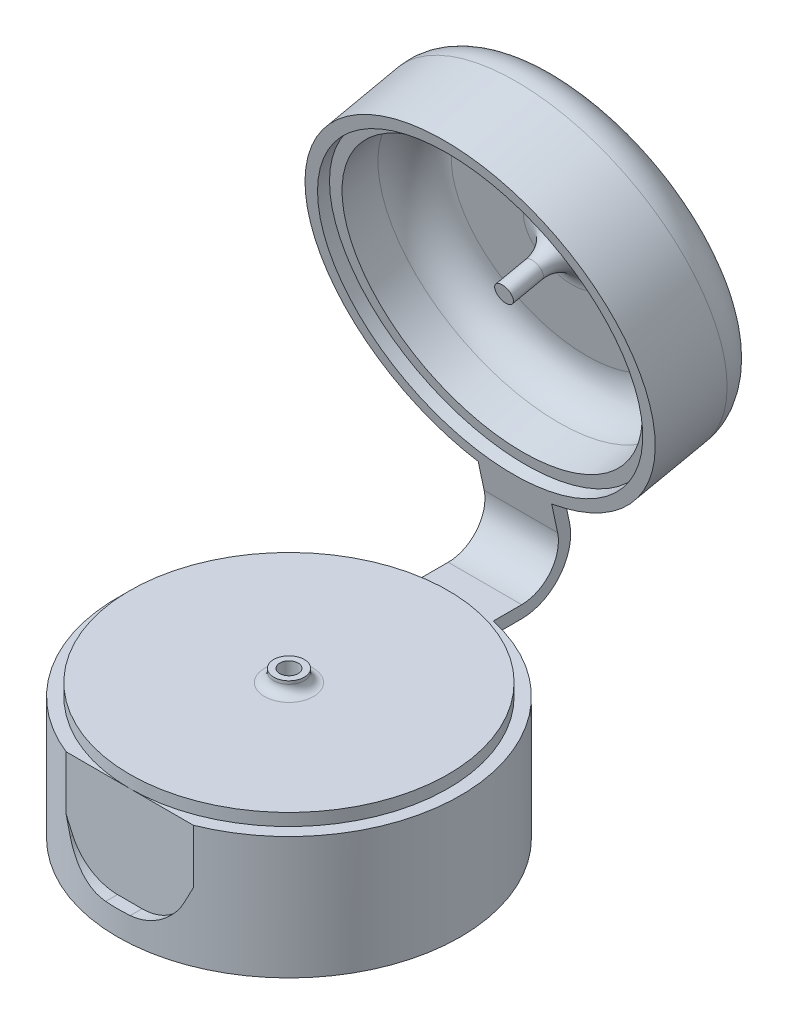
SolidWorks part; units mm, degrees
material "Polyethylene Cross-Linked"
ref_plane "Front Plane" through (0, 0, 0) normal (0, 0, 1) x (1, 0, 0)
ref_plane "Top Plane" through (0, 0, 0) normal (0, 1, 0) x (1, 0, 0)
ref_plane "Right Plane" through (0, 0, 0) normal (1, 0, 0) x (0, 0, -1)
sketch "Sketch1" plane through (0, 0, 0) normal (1, 0, 0) x (0, 0, -1)
  line L0 (0, 0) -> (0, -5.1961) construction
  line L1 (-2, 0) -> (-13, 0)
  line L2 (-13, 0) -> (-13, -1)
  line L3 (-13, -1) -> (-14, -1)
  line L4 (-14, -1) -> (-14, -11)
  line L7 (-14, -11) -> (-12, -11)
  line L8 (-12, -11) -> (-12, -2)
  line L9 (-12, -2) -> (-2, -2)
  line L13 (-2, 0) -> (-2, -2)
  dimension "D2" = 1
  dimension "D3" = 1
  dimension "D1" = 28
  dimension "D4" = 11
  dimension "D5" = 2
  dimension "D6" = 2
  dimension "D7" = 4
revolve "Revolve1" add sketch "Sketch1" angle 360 about L0
ref_plane "Plane1" through (0, 0, 13) normal (0, 0, 1) x (1, 0, 0)
sketch "Sketch3" plane through (0, 0, 13) normal (0, 0, 1) x (1, 0, 0)
  line L0 (0, -1) -> (0, -9) construction
  line L1 (14, -1) -> (-14, -1) construction
  line L2 (1, -9) -> (-1, -9)
  line L3 (-4.6542, -6.6269) -> (-7.1595, -1)
  line L4 (-7.1595, -1) -> (7.1595, -1)
  line L5 (-14, -11) -> (14, -11) construction
  line L6 (4.6542, -6.6269) -> (7.1595, -1)
  arc A0 (-1, -9) -> (-4.6542, -6.6269) centre (-1, -5) cw
  arc A1 (1, -9) -> (4.6542, -6.6269) centre (1, -5) ccw
  dimension "D1" = 4
  dimension "D2" = 2
  dimension "D3" = 48
  dimension "D4" = 2
extrude "Cut-Extrude1" cut sketch "Sketch3" along normal blind 8.5 from surface at 0 starting at plane "Plane1"
sketch "Sketch4" plane through (0, 0, 0) normal (1, 0, 0) x (0, 0, -1)
  line L0 (13, -1) -> (16, -1)
  line L1 (14, -1) -> (-13, -1) construction
  line L2 (18.9344, 2.6237) -> (18.3107, 5.5582)
  line L3 (18.3107, 5.5582) -> (19.2889, 5.7661)
  line L4 (19.2889, 5.7661) -> (19.9126, 2.8316)
  line L5 (16, -2) -> (13, -2)
  line L6 (13, -2) -> (13, -1)
  arc A0 (16, -1) -> (18.9344, 2.6237) centre (16, 2) ccw
  arc A1 (19.9126, 2.8316) -> (16, -2) centre (16, 2) cw
  dimension "D3" = 3
  dimension "D1" = 1
  dimension "D4" = 3
  dimension "D5" = 3
  dimension "D2" = 78
extrude "Boss-Extrude1" add sketch "Sketch4" along normal mid plane 6
sketch "Sketch5" plane through (0, 0, 0) normal (1, 0, 0) x (0, 0, -1)
  line L0 (18.5186, 4.58) -> (27.3219, 6.4512)
  line L1 (18.3107, 5.5582) -> (18.9344, 2.6237) construction
  line L2 (27.3219, 6.4512) -> (24.4112, 20.1453)
  line L3 (24.4112, 20.1453) -> (22.4549, 19.7295) construction
  line L6 (22.4549, 19.7295) -> (24.9498, 7.9917)
  line L7 (24.9498, 7.9917) -> (19.0809, 6.7442)
  line L8 (19.0809, 6.7442) -> (19.2889, 5.7661)
  line L9 (19.2889, 5.7661) -> (18.3107, 5.5582)
  line L10 (18.3107, 5.5582) -> (18.5186, 4.58)
  line L11 (24.4112, 20.1453) -> (22.4549, 19.7295)
  dimension "D2" = 1
  dimension "D3" = 1
  dimension "D1" = 28
  dimension "D7" = 2
  dimension "D5" = 9
  dimension "D4" = 2
revolve "Revolve2" add sketch "Sketch5" angle 360 about L3
fillet "Fillet1" radius 3 2 edges at (0, 31.4672, -19.9599) (0, 33.8394, -21.5004)
sketch "Sketch6" plane through (0, 0, 0) normal (1, 0, 0) x (0, 0, -1)
  line L0 (0, 0) -> (0, 1) construction
  line L2 (0.75, 1) -> (0.75, -0.75)
  line L4 (2, -2) -> (2, 0)
  line L5 (2, 0) -> (-2, 0) construction
  line L6 (13, 0) -> (-13, 0) construction
  line L7 (1.25, 0.75) -> (1.25, 1)
  line L8 (1.25, 1) -> (0.75, 1)
  line L9 (-2, -2) -> (2, -2) construction
  arc A1 (2, 0) -> (1.25, 0.75) centre (2, 0.75) cw
  arc A2 (0.75, -0.75) -> (2, -2) centre (2, -0.75) ccw
  dimension "D1" = 0.75
  dimension "D3" = 1.25
  dimension "D2" = 1
revolve "Revolve3" add sketch "Sketch6" angle 360 about L0
sketch "Sketch7" plane through (0, 0, 0) normal (1, 0, 0) x (0, 0, -1)
  line L2 (22.4549, 19.7295) -> (17.5603, 18.6891)
  line L3 (20.5837, 28.5328) -> (24.3261, 10.9262) construction
  line L4 (17.5603, 18.6891) -> (17.4044, 19.4227)
  line L5 (17.4044, 19.4227) -> (19.8536, 19.9433)
  line L6 (21.7792, 22.9085) -> (22.4549, 19.7295)
  arc A0 (19.8536, 19.9433) -> (21.7792, 22.9085) centre (19.3338, 22.3887) ccw
  dimension "D2" = 2.5
  dimension "D1" = 5.0039
  dimension "D3" = 0.75
revolve "Revolve4" add sketch "Sketch7" angle 360 about L2
equation "\"A\"= 28"
equation "\"D1@Sketch1\"=\"A\""
equation "\"B\"= 1"
equation "\"D2@Sketch1\"=\"B\""
equation "\"C\"= 78"
equation "\"D3@Sketch1\"=\"B\""
equation "\"D1@Sketch5\"=\"A\""
equation "\"D2@Sketch5\"=\"B\""
equation "\"D3@Sketch5\"=\"B\""
equation "\"D2@Sketch4\"=\"C\""
equation "\"D5@Sketch1\"=\"B\"*2"
equation "\"D6@Sketch1\"=\"B\"*2"
equation "\"D4@Sketch5\"=\"B\"*2"
equation "\"D7@Sketch5\"=\"B\"*2"
equation "\"D1@Sketch4\"=\"B\""
